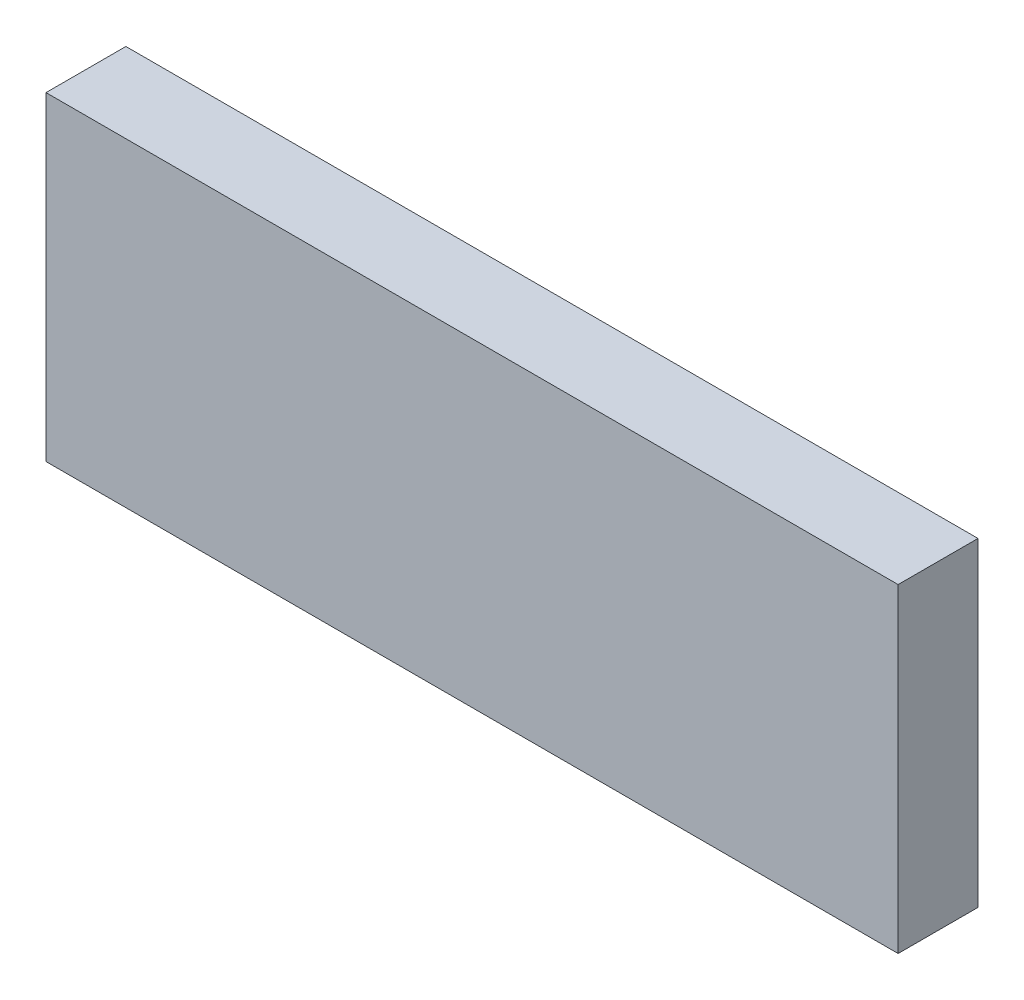
SolidWorks part; units mm, degrees
ref_plane "Front Plane" through (0, 0, 0) normal (0, 0, 1) x (1, 0, 0)
ref_plane "Top Plane" through (0, 0, 0) normal (0, 1, 0) x (1, 0, 0)
ref_plane "Right Plane" through (0, 0, 0) normal (1, 0, 0) x (0, 0, -1)
sketch "Sketch1" plane through (0, 0, 0) normal (0, 0, 1) x (1, 0, 0)
  line L1 (0, 0) -> (203.2, 0)
  line L2 (0, 0) -> (0, 76.2)
  line L3 (0, 76.2) -> (203.2, 76.2)
  line L4 (203.2, 0) -> (203.2, 76.2)
  dimension "D1" = 203.2
  dimension "D2" = 76.2
extrude "Boss-Extrude1" add sketch "Sketch1" along normal blind 19.05
ref_plane "mid" through (0, 0, 9.525) normal (0, 0, -1) x (-1, 0, 0)
